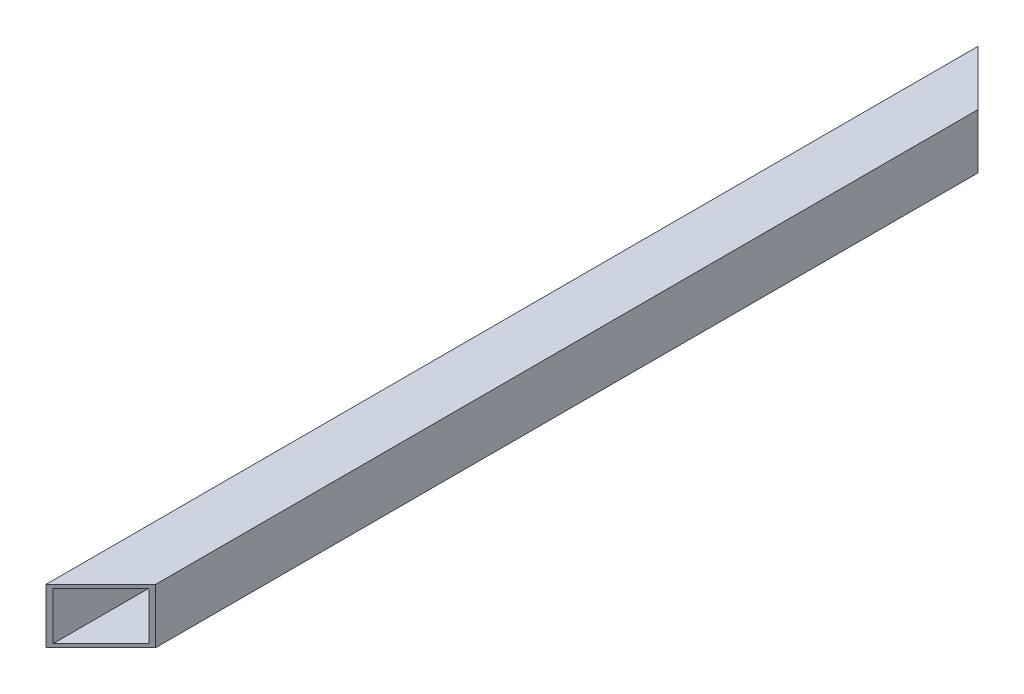
SolidWorks part; units mm, degrees
ref_plane "Front Plane" through (0, 0, 0) normal (0, 0, 1) x (1, 0, 0)
ref_plane "Top Plane" through (0, 0, 0) normal (0, 1, 0) x (1, 0, 0)
ref_plane "Right Plane" through (0, 0, 0) normal (1, 0, 0) x (0, 0, -1)
sketch "Sketch1" plane through (0, 0, 0) normal (0, 0, 1) x (1, 0, 0)
  line L1 (-11.1125, -11.1125) -> (11.1125, -11.1125)
  line L2 (-11.1125, -11.1125) -> (-11.1125, 11.1125)
  line L3 (-11.1125, 11.1125) -> (11.1125, 11.1125)
  line L4 (11.1125, -11.1125) -> (11.1125, 11.1125)
  line L5 (-11.1125, -11.1125) -> (11.1125, 11.1125) construction
  line L6 (-11.1125, 11.1125) -> (11.1125, -11.1125) construction
  line L7 (-12.7, -12.7) -> (12.7, -12.7)
  line L8 (-12.7, -12.7) -> (-12.7, 12.7)
  line L9 (-12.7, 12.7) -> (12.7, 12.7)
  line L10 (12.7, -12.7) -> (12.7, 12.7)
  line L11 (-12.7, -12.7) -> (12.7, 12.7) construction
  line L12 (-12.7, 12.7) -> (12.7, -12.7) construction
  point P0 (0, 0)
  point P6 (0, 0)
  dimension "D1" = 1.5875
  dimension "D2" = 25.4
extrude "Boss-Extrude1" add sketch "Sketch1" along normal blind 431.8
ref_plane "Plane1" through (0, 0, 215.9) normal (0, 0, 1) x (1, 0, 0)
sketch "Sketch2" plane through (0, 12.7, 0) normal (0, 1, 0) x (1, 0, 0)
  line L0 (12.7, 0) -> (12.7, -25.4)
  line L1 (12.7, -431.8) -> (12.7, 0) construction
  line L2 (12.7, -25.4) -> (-12.7, 0)
  line L3 (-12.7, 0) -> (12.7, 0)
extrude "Cut-Extrude1" cut sketch "Sketch2" against normal through all
mirror "Mirror1" about plane through (0, 0, 215.9) normal (0, 0, 1) of "Cut-Extrude1"
